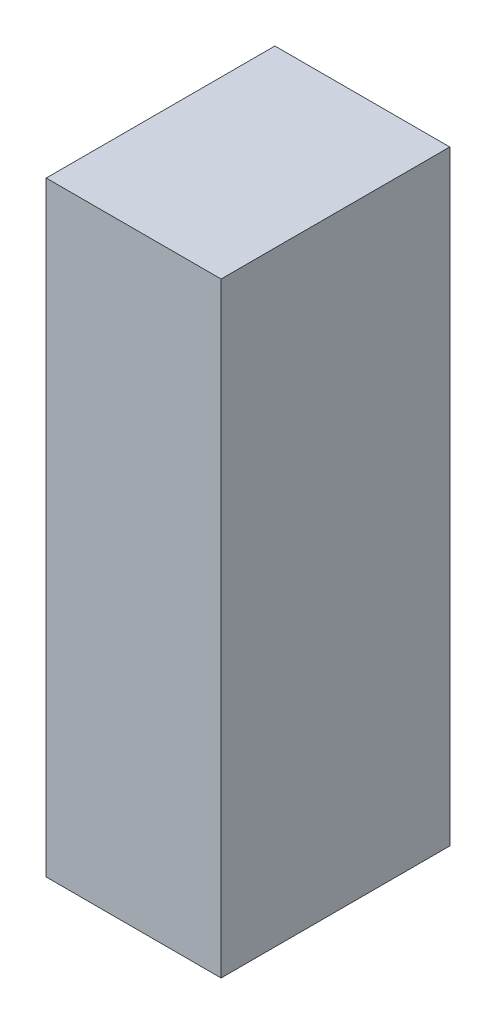
SolidWorks part; units mm, degrees
ref_plane "Front Plane" through (0, 0, 0) normal (0, 0, 1) x (1, 0, 0)
ref_plane "Top Plane" through (0, 0, 0) normal (0, 1, 0) x (1, 0, 0)
ref_plane "Right Plane" through (0, 0, 0) normal (1, 0, 0) x (0, 0, -1)
sketch "草圖1" plane through (0, 0, 0) normal (0, 0, 1) x (1, 0, 0)
  line L0 (-6.5, -22.5) -> (6.5, -22.5)
  line L1 (6.5, -22.5) -> (6.5, 22.5)
  line L2 (6.5, 22.5) -> (-6.5, 22.5)
  line L3 (-6.5, 22.5) -> (-6.5, -22.5)
extrude "填料-伸長1" add sketch "草圖1" along normal blind 17
